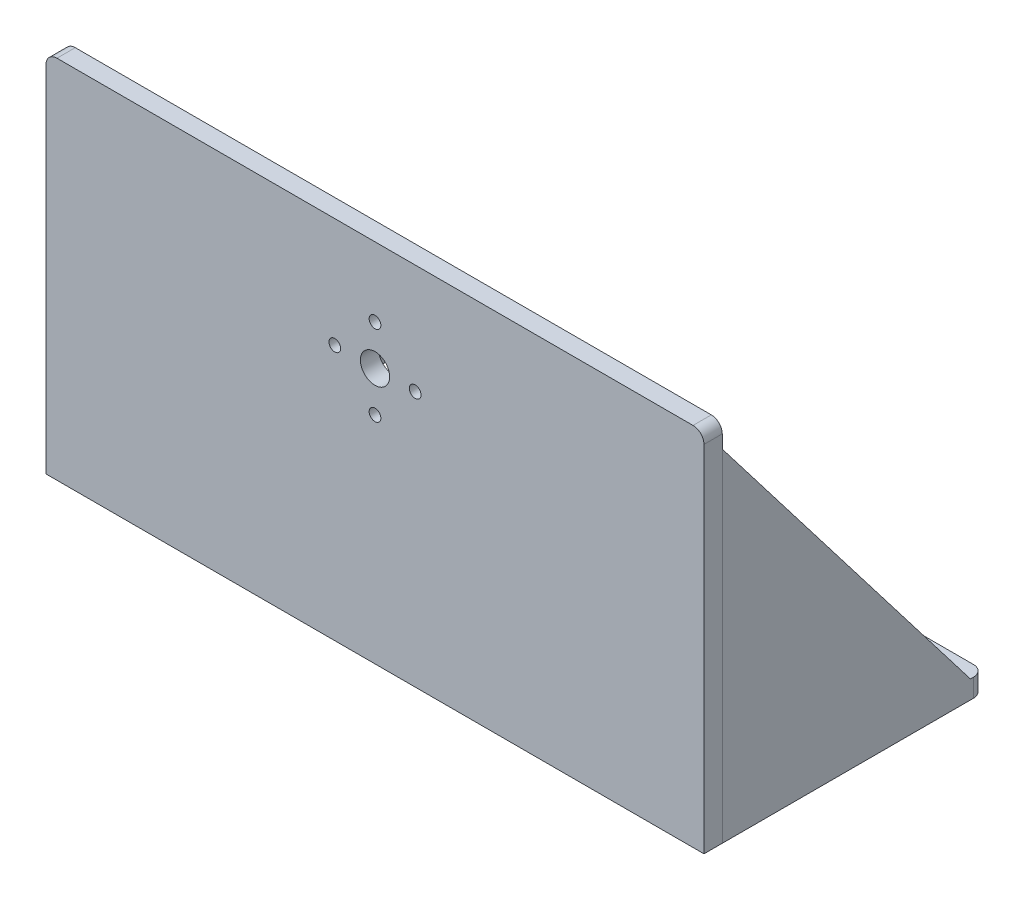
SolidWorks part; units mm, degrees
ref_plane "Alzado" through (0, 0, 0) normal (0, 0, 1) x (1, 0, 0)
ref_plane "Planta" through (0, 0, 0) normal (0, 1, 0) x (1, 0, 0)
ref_plane "Vista lateral" through (0, 0, 0) normal (1, 0, 0) x (0, 0, -1)
sketch "Croquis1" plane through (0, 0, 0) normal (0, 0, 1) x (1, 0, 0)
  line L0 (0, 0.8576) -> (0, 50000.8576) construction
  line L2 (-90, 30) -> (90, 30)
  line L3 (-90, 30) -> (-90, -70)
  line L4 (-90, -70) -> (90, -70)
  line L5 (90, 30) -> (90, -70)
  circle A0 centre (0, 0) radius 4
  circle A1 centre (0, 11) radius 1.6
  circle A2 centre (11, 0) radius 1.6
  circle A3 centre (0, -11) radius 1.6
  circle A4 centre (-11, 0) radius 1.6
  point P16 (0, 0)
  point P18 (0, 30)
  dimension "D1" = 8
  dimension "D2" = 3.2
  dimension "D3" = 11
  dimension "D5" = 30
  dimension "D6" = 180
  dimension "D7" = 100
  dimension "D4" = 4
extrude "Saliente-Extruir1" add sketch "Croquis1" along normal blind 5
sketch "Croquis2" plane through (90, 0, 0) normal (1, 0, 0) x (0, 0, -1)
  line L0 (0, -70) -> (0, 23.3833)
  line L1 (0, 23.3833) -> (71.7254, -70)
  line L2 (71.7254, -70) -> (0, -70)
  line L3 (0, -70) -> (0, 30) construction
  point P5 (0, 23.3833)
  point P9 (0, -70)
  point P10 (0, -70)
extrude "Saliente-Extruir2" add sketch "Croquis2" against normal blind 5 separate body
sketch "Croquis3" plane through (0, -70, 0) normal (0, -1, 0) x (1, 0, 0)
  line L0 (90, 0) -> (90, -71.7254) construction
  line L1 (90, -6.2849) -> (70, -6.2849)
  line L2 (90, -6.2849) -> (90, -71.7254)
  line L3 (90, -71.7254) -> (70, -71.7254)
  line L4 (70, -6.2849) -> (70, -71.7254)
  circle A0 centre (77.673, -22.4004) radius 2.5
  circle A1 centre (77.673, -49.7593) radius 2.5
  point P10 (77.673, -22.4004)
  point P11 (77.673, -49.7593)
  point P12 (0, 0)
  dimension "D1" = 5
  dimension "D2" = 20
extrude "Saliente-Extruir3" add sketch "Croquis3" against normal blind 5
fillet "Redondeo1" radius 3 3 edges at (90, -67.5, -71.7254) (70, -67.5, -71.7254) (70, -67.5, -6.2849)
fillet "Redondeo2" radius 3 2 edges at (90, 30, 2.5) (-90, 30, 2.5)
mirror "Simetría4" about plane through (0, 0, 0) normal (1, 0, 0) of bodies 103
